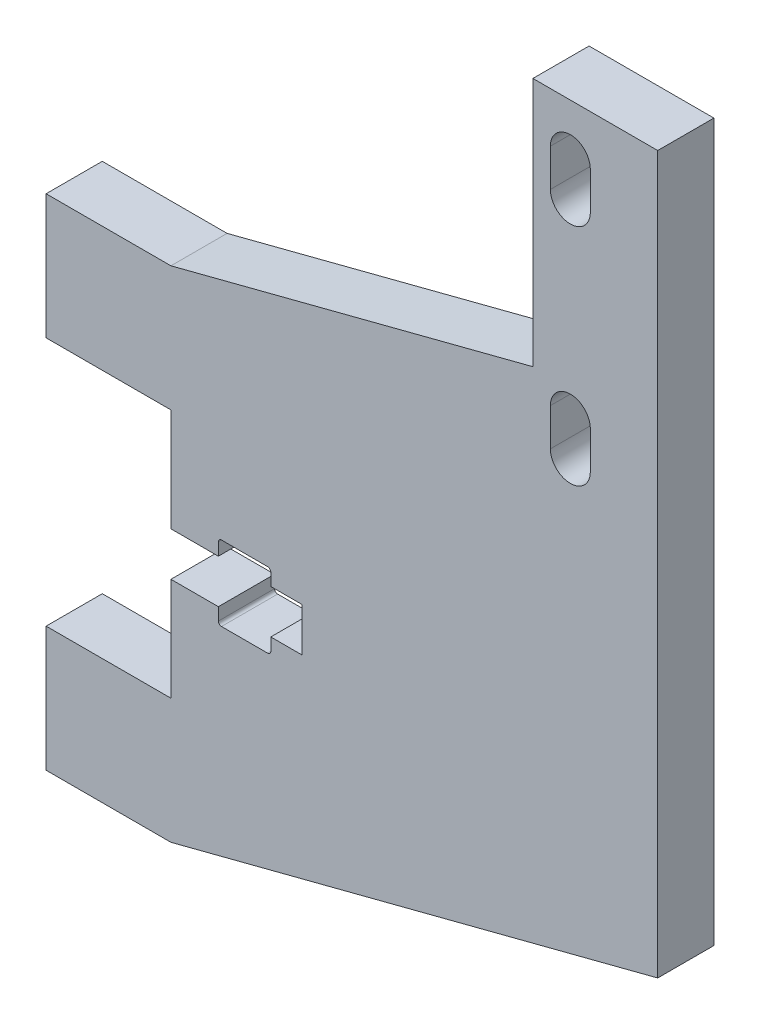
SolidWorks part; units mm, degrees
ref_plane "Front Plane" through (0, 0, 0) normal (0, 0, 1) x (1, 0, 0)
ref_plane "Top Plane" through (0, 0, 0) normal (0, 1, 0) x (1, 0, 0)
ref_plane "Right Plane" through (0, 0, 0) normal (1, 0, 0) x (0, 0, -1)
sketch "Sketch1" plane through (0, 0, 0) normal (0, 0, 1) x (1, 0, 0)
  line L0 (29, 2.5) -> (0, -5)
  line L1 (0, -5) -> (-10, -5)
  line L2 (-10, -5) -> (-10, -15)
  line L3 (-10, -15) -> (0, -15)
  line L4 (0, -15) -> (0, -35)
  line L5 (0, -35) -> (-10, -35)
  line L6 (-10, -35) -> (-10, -45)
  line L7 (-10, -45) -> (0, -45)
  line L10 (0, -45) -> (39, -34.9138)
  line L11 (39, -34.9138) -> (39, 22.5)
  line L12 (39, 22.5) -> (29, 22.5)
  line L13 (29, 22.5) -> (29, 2.5)
  line L15 (0, -5) -> (0, -45) construction
  line L16 (-10, -10) -> (0, -10) construction
  line L17 (-10, -40) -> (0, -40) construction
  line L18 (-10, -15) -> (-10, -35) construction
  line L19 (-10, -25) -> (0, -25) construction
  dimension "D1" = 10
  dimension "D2" = 10
  dimension "D3" = 10
  dimension "D4" = 10
  dimension "D5" = 15
  dimension "D8" = 10
  dimension "D9" = 20
  dimension "D10" = 29
  dimension "D6" = 67.5
extrude "Boss-Extrude1" add sketch "Sketch1" along normal blind 4.5
sketch "Sketch2" plane through (0, 0, 4.5) normal (0, 0, 1) x (1, 0, 0)
  line L0 (0, -25) -> (39, -25) construction
  line L1 (0, -15) -> (0, -35) construction
  line L3 (10.5, -26.75) -> (10.5, -23.25) construction
  line L4 (10.5, -23.25) -> (0, -23.25) construction
  line L5 (0, -26.75) -> (0, -23.25)
  line L6 (0, -23.25) -> (3.8, -23.25)
  line L7 (3.8, -23.25) -> (3.8, -22.25)
  line L8 (4.05, -22) -> (7.75, -22)
  line L9 (8, -22.25) -> (8, -23.25)
  line L10 (8, -23.25) -> (10.5, -23.25)
  line L11 (10.5, -23.25) -> (10.5, -26.75)
  line L12 (10.5, -26.75) -> (0, -26.75) construction
  line L13 (8, -26.75) -> (10.5, -26.75)
  line L14 (8, -27.75) -> (8, -26.75)
  line L15 (4.05, -28) -> (7.75, -28)
  line L16 (3.8, -26.75) -> (3.8, -27.75)
  line L17 (0, -26.75) -> (3.8, -26.75)
  line L18 (39, -34.9138) -> (39, 22.5) construction
  arc A0 (7.75, -22) -> (8, -22.25) centre (7.75, -22.25) cw
  arc A1 (3.8, -22.25) -> (4.05, -22) centre (4.05, -22.25) cw
  arc A2 (3.8, -27.75) -> (4.05, -28) centre (4.05, -27.75) ccw
  arc A3 (7.75, -28) -> (8, -27.75) centre (7.75, -27.75) ccw
  point P15 (8, -22)
  point P18 (3.8, -22)
  point P27 (10.5, -25)
  point P29 (3.8, -28)
  point P30 (8, -28)
  dimension "D6" = 0.25
  dimension "D1" = 10.5
  dimension "D2" = 1.75
  dimension "D3" = 8
  dimension "D4" = 4.2
  dimension "D5" = 3
  dimension "D7" = 0
extrude "screw-cutout" cut sketch "Sketch2" against normal through all
sketch "Sketch3" plane through (0, 0, 4.5) normal (0, 0, 1) x (1, 0, 0)
  line L0 (32, 55) -> (32, -45) construction
  line L1 (39, 22.5) -> (29, 22.5) construction
  line L2 (32, 18.5) -> (32, 15.5) construction
  line L3 (29, 22.5) -> (29, 2.5) construction
  line L4 (33.6, 18.5) -> (33.6, 15.5)
  line L5 (-10, -45) -> (0, -45) construction
  line L6 (30.4, 18.5) -> (30.4, 15.5)
  line L7 (32, 0.5) -> (32, -2.5) construction
  line L8 (33.6, 0.5) -> (33.6, -2.5)
  line L9 (30.4, 0.5) -> (30.4, -2.5)
  arc A0 (33.6, 0.5) -> (30.4, 0.5) centre (32, 0.5) ccw
  arc A2 (33.6, 18.5) -> (30.4, 18.5) centre (32, 18.5) ccw
  arc A3 (30.4, 15.5) -> (33.6, 15.5) centre (32, 15.5) ccw
  arc A4 (30.4, -2.5) -> (33.6, -2.5) centre (32, -2.5) ccw
  point P8 (32, 17)
  point P14 (32, -1)
  dimension "D7" = 0
  dimension "D8" = 1.6
  dimension "D1" = 1.6
  dimension "D2" = 18
  dimension "D3" = 4
  dimension "D6" = 3
  dimension "D9" = 3
  dimension "D10" = 3
extrude "Cut-Extrude2" cut sketch "Sketch3" against normal through all
sketch "Sketch4" plane through (0, 0, 4.5) normal (0, 0, 1) x (1, 0, 0)
  line L0 (32, 0.5) -> (32, 18.5) construction
  line L1 (32, 9.5) -> (29, 9.5) construction
  line L2 (29, 22.5) -> (29, 2.5) construction
  line L4 (30, 13.5) -> (28, 13.5)
  line L5 (30, 13.5) -> (30, 5.5)
  line L6 (30, 5.5) -> (28, 5.5)
  line L7 (28, 13.5) -> (28, 5.5)
  line L8 (30, 13.5) -> (28, 5.5) construction
  line L9 (30, 5.5) -> (28, 13.5) construction
  arc A2 (33.6, 0.5) -> (30.4, 0.5) centre (32, 0.5) ccw construction
  arc A4 (33.6, 18.5) -> (30.4, 18.5) centre (32, 18.5) ccw construction
  point P11 (29, 9.5)
  dimension "D1" = 8
  dimension "D2" = 2
  dimension "D3" = 3
  dimension "D4" = 0
  dimension "D5" = 0
equation "\"X-ROD-SPACING\"=45"
equation "\"Y-ROD-SPACING\"=75"
equation "\"Z-ROD-SPACING\"=17.5"
equation "\"Y-BED-OFFSET\"=2"
equation "\"Y-BED-ROD-INSET\"=3.5"
equation "\"T-SLOT-NUT-FILLET-RADIUS\"=0.25"
equation "\"T-SLOT-SCREW-SHAFT-RADIUS\"=1.75"
equation "\"T-SLOT-SCREW-SHAFT-CUTOUT-LENGTH\"=10.5"
equation "\"T-SLOT-NUT-DEPTH\"=4.2"
equation "\"T-SLOT-NUT-WIDTH\"=3"
equation "\"T-SLOT-NUT-END-DISTANCE\"=8"
equation "\"ACRYLIC-THICKNESS\"=10"
equation "\"ACRYLIC-THICKNESS2\"=4.5"
equation "\"ACRYLIC-TAB-CUTOUT-SIZE\"=\"ACRYLIC-THICKNESS\"+\"ACRYLIC-TAB-TOLERANCE\"*2"
equation "\"ACRYLIC-TAB-WIDTH\"=\"ACRYLIC-THICKNESS\""
equation "\"ACRYLIC-M3-HOLE\"=3.2"
equation "\"SMOOTHROD-CAP-SCREW-DISTANCE\"=20"
equation "\"FRAME-WIDTH-INNER\"=370"
equation "\"NEMA17-HOLE-SPACING\"=31"
equation "\"NEMA17-CENTRAL-CUTOUT\"=22.5"
equation "\"Z-BRACKET-REACH\"=55"
equation "\"Z-ROD-INSET\"=16"
equation "\"TOP-BRACKET-SPACING\"=40"
equation "\"SMOOTHROD-X-LENGTH\"=350"
equation "\"SMOOTHROD-Y-LENGTH\"=350"
equation "\"SMOOTHROD-Z-LENGTH\"=350"
equation "\"SMOOTHROD-TIGHTENING-HEADROOM\"=1"
equation "\"LEADSCREW-Z-LENGTH\"=300"
equation "\"SCREW-LENGTH-FRAME\"=\"ACRYLIC-THICKNESS\" + 10"
equation "\"SCREW-HEAD-RADIUS\"=6"
equation "\"PRINTED-X-SMOOTHROD-DIAMETER\"=8.2"
equation "\"PRINTED-X-SMOOTHROD-CUTOUT\"=10"
equation "\"PRINTED-X-BASE-HEIGHT\"=10"
equation "\"PRINTED-LM8UU-CUTOUT-SIZE\"=15.25"
equation "\"PRINTED-LM8UU-CUTOUT-LENGTH\"=24.5"
equation "\"PRINTED-X-IDLER-HEIGHT\"=16"
equation "\"PSU-MOUNTING-WIDTH\"=95"
equation "\"PSU-MOUNTING-HEIGHT\"=177"
equation "\"Y-BELT-TO-ROD-DISTANCE\"=20"
equation "\"SPOOL-HOLDER-ROD-SPACING\"=150"
equation "\"D1@Sketch1\"=\"ACRYLIC-TAB-WIDTH\""
equation "\"D2@Sketch1\"=\"ACRYLIC-TAB-WIDTH\""
equation "\"D3@Sketch1\"=\"ACRYLIC-THICKNESS\""
equation "\"D4@Sketch1\"=\"ACRYLIC-THICKNESS\""
equation "\"D1@Boss-Extrude1\"=\"ACRYLIC-THICKNESS2\""
equation "\"D1@Sketch2\"=\"T-SLOT-SCREW-SHAFT-CUTOUT-LENGTH\""
equation "\"D2@Sketch2\"=\"T-SLOT-SCREW-SHAFT-RADIUS\""
equation "\"D3@Sketch2\"=\"T-SLOT-NUT-END-DISTANCE\""
equation "\"D4@Sketch2\"=\"T-SLOT-NUT-DEPTH\""
equation "\"D5@Sketch2\"=\"T-SLOT-NUT-WIDTH\""
equation "\"D6@Sketch2\"=\"T-SLOT-NUT-FILLET-RADIUS\""
equation "\"D1@Sketch3\"=\"ACRYLIC-M3-HOLE\"/2"
equation "\"D8@Sketch3\"=\"ACRYLIC-M3-HOLE\"/2"
